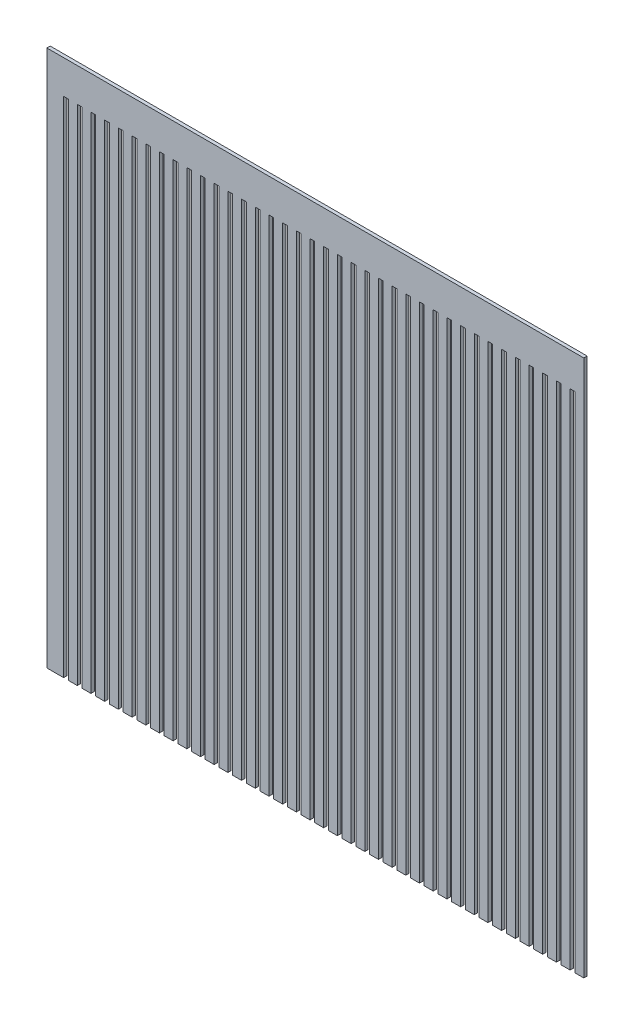
SolidWorks part; units mm, degrees
ref_plane "前视基准面" through (0, 0, 0) normal (0, 0, 1) x (1, 0, 0)
ref_plane "上视基准面" through (0, 0, 0) normal (0, 1, 0) x (1, 0, 0)
ref_plane "右视基准面" through (0, 0, 0) normal (1, 0, 0) x (0, 0, -1)
sketch "草图1" plane through (0, 0, 0) normal (0, 0, 1) x (1, 0, 0)
  line L0 (-74.9927, 70) -> (-74.9927, -80)
  line L2 (-79.9927, -80) -> (-79.9927, 80)
  line L3 (-79.9927, 80) -> (80.0073, 80)
  line L4 (80.0073, -80) -> (80.0073, 80)
  line L5 (-69.5137, -80) -> (-69.5137, 70)
  line L6 (-70.9137, 70) -> (-70.9137, -80)
  line L7 (-70.9137, 70) -> (-69.5137, 70)
  line L8 (-73.5927, -80) -> (-73.5927, 70)
  line L9 (-74.9927, -80) -> (-79.9927, -80)
  line L10 (-74.9927, 70) -> (-73.5927, 70)
  line L11 (-65.4348, -80) -> (-65.4348, 70)
  line L13 (-74.2927, -80) -> (-74.2927, 72.603) construction
  line L14 (-66.8348, 70) -> (-66.8348, -80)
  line L15 (-66.8348, 70) -> (-65.4348, 70)
  line L17 (-73.5927, 70) -> (-73.5927, -80)
  line L19 (-74.9927, -80) -> (-79.9927, -80)
  line L20 (-61.3558, -80) -> (-61.3558, 70)
  line L21 (-62.7558, 70) -> (-62.7558, -80)
  line L22 (-62.7558, 70) -> (-61.3558, 70)
  line L23 (-57.2769, -80) -> (-57.2769, 70)
  line L24 (-58.6769, 70) -> (-58.6769, -80)
  line L25 (-58.6769, 70) -> (-57.2769, 70)
  line L26 (-53.1979, -80) -> (-53.1979, 70)
  line L27 (-54.5979, 70) -> (-54.5979, -80)
  line L28 (-54.5979, 70) -> (-53.1979, 70)
  line L29 (-49.119, -80) -> (-49.119, 70)
  line L30 (-50.519, 70) -> (-50.519, -80)
  line L31 (-50.519, 70) -> (-49.119, 70)
  line L32 (-45.04, -80) -> (-45.04, 70)
  line L33 (-46.44, 70) -> (-46.44, -80)
  line L34 (-46.44, 70) -> (-45.04, 70)
  line L35 (-40.9611, -80) -> (-40.9611, 70)
  line L36 (-42.3611, 70) -> (-42.3611, -80)
  line L37 (-42.3611, 70) -> (-40.9611, 70)
  line L38 (-36.8821, -80) -> (-36.8821, 70)
  line L39 (-38.2821, 70) -> (-38.2821, -80)
  line L40 (-38.2821, 70) -> (-36.8821, 70)
  line L41 (-32.8032, -80) -> (-32.8032, 70)
  line L42 (-34.2032, 70) -> (-34.2032, -80)
  line L43 (-34.2032, 70) -> (-32.8032, 70)
  line L44 (-28.7242, -80) -> (-28.7242, 70)
  line L45 (-30.1242, 70) -> (-30.1242, -80)
  line L46 (-30.1242, 70) -> (-28.7242, 70)
  line L47 (-24.6453, -80) -> (-24.6453, 70)
  line L48 (-26.0453, 70) -> (-26.0453, -80)
  line L49 (-26.0453, 70) -> (-24.6453, 70)
  line L50 (-20.5663, -80) -> (-20.5663, 70)
  line L51 (-21.9663, 70) -> (-21.9663, -80)
  line L52 (-21.9663, 70) -> (-20.5663, 70)
  line L53 (-16.4874, -80) -> (-16.4874, 70)
  line L54 (-17.8874, 70) -> (-17.8874, -80)
  line L55 (-17.8874, 70) -> (-16.4874, 70)
  line L56 (-12.4084, -80) -> (-12.4084, 70)
  line L57 (-13.8084, 70) -> (-13.8084, -80)
  line L58 (-13.8084, 70) -> (-12.4084, 70)
  line L59 (-8.3295, -80) -> (-8.3295, 70)
  line L60 (-9.7295, 70) -> (-9.7295, -80)
  line L61 (-9.7295, 70) -> (-8.3295, 70)
  line L62 (-4.2506, -80) -> (-4.2506, 70)
  line L63 (-5.6506, 70) -> (-5.6506, -80)
  line L64 (-5.6506, 70) -> (-4.2506, 70)
  line L65 (-0.1716, -80) -> (-0.1716, 70)
  line L66 (-1.5716, 70) -> (-1.5716, -80)
  line L67 (-1.5716, 70) -> (-0.1716, 70)
  line L68 (3.9073, -80) -> (3.9073, 70)
  line L69 (2.5073, 70) -> (2.5073, -80)
  line L70 (2.5073, 70) -> (3.9073, 70)
  line L71 (7.9863, -80) -> (7.9863, 70)
  line L72 (6.5863, 70) -> (6.5863, -80)
  line L73 (6.5863, 70) -> (7.9863, 70)
  line L74 (12.0652, -80) -> (12.0652, 70)
  line L75 (10.6652, 70) -> (10.6652, -80)
  line L76 (10.6652, 70) -> (12.0652, 70)
  line L77 (16.1442, -80) -> (16.1442, 70)
  line L78 (14.7442, 70) -> (14.7442, -80)
  line L79 (14.7442, 70) -> (16.1442, 70)
  line L80 (20.2231, -80) -> (20.2231, 70)
  line L81 (18.8231, 70) -> (18.8231, -80)
  line L82 (18.8231, 70) -> (20.2231, 70)
  line L83 (24.3021, -80) -> (24.3021, 70)
  line L84 (22.9021, 70) -> (22.9021, -80)
  line L85 (22.9021, 70) -> (24.3021, 70)
  line L86 (28.381, -80) -> (28.381, 70)
  line L87 (26.981, 70) -> (26.981, -80)
  line L88 (26.981, 70) -> (28.381, 70)
  line L89 (32.46, -80) -> (32.46, 70)
  line L90 (31.06, 70) -> (31.06, -80)
  line L91 (31.06, 70) -> (32.46, 70)
  line L92 (36.5389, -80) -> (36.5389, 70)
  line L93 (35.1389, 70) -> (35.1389, -80)
  line L94 (35.1389, 70) -> (36.5389, 70)
  line L95 (40.6179, -80) -> (40.6179, 70)
  line L96 (39.2179, 70) -> (39.2179, -80)
  line L97 (39.2179, 70) -> (40.6179, 70)
  line L98 (44.6968, -80) -> (44.6968, 70)
  line L99 (43.2968, 70) -> (43.2968, -80)
  line L100 (43.2968, 70) -> (44.6968, 70)
  line L101 (48.7758, -80) -> (48.7758, 70)
  line L102 (47.3758, 70) -> (47.3758, -80)
  line L103 (47.3758, 70) -> (48.7758, 70)
  line L104 (52.8547, -80) -> (52.8547, 70)
  line L105 (51.4547, 70) -> (51.4547, -80)
  line L106 (51.4547, 70) -> (52.8547, 70)
  line L107 (56.9337, -80) -> (56.9337, 70)
  line L108 (55.5337, 70) -> (55.5337, -80)
  line L109 (55.5337, 70) -> (56.9337, 70)
  line L110 (61.0126, -80) -> (61.0126, 70)
  line L111 (59.6126, 70) -> (59.6126, -80)
  line L112 (59.6126, 70) -> (61.0126, 70)
  line L113 (65.0916, -80) -> (65.0916, 70)
  line L114 (63.6916, 70) -> (63.6916, -80)
  line L115 (63.6916, 70) -> (65.0916, 70)
  line L116 (69.1705, -80) -> (69.1705, 70)
  line L117 (67.7705, 70) -> (67.7705, -80)
  line L118 (67.7705, 70) -> (69.1705, 70)
  line L119 (73.2494, -80) -> (73.2494, 70)
  line L120 (71.8494, 70) -> (71.8494, -80)
  line L121 (71.8494, 70) -> (73.2494, 70)
  line L122 (77.3284, -80) -> (77.3284, 70)
  line L123 (75.9284, 70) -> (75.9284, -80)
  line L124 (75.9284, 70) -> (77.3284, 70)
  line L125 (-73.5927, -80) -> (-70.9137, -80)
  line L126 (-69.5137, -80) -> (-66.8348, -80)
  line L127 (-65.4348, -80) -> (-62.7558, -80)
  line L128 (-61.3558, -80) -> (-58.6769, -80)
  line L129 (-57.2769, -80) -> (-54.5979, -80)
  line L130 (-53.1979, -80) -> (-50.519, -80)
  line L131 (-49.119, -80) -> (-46.44, -80)
  line L132 (-45.04, -80) -> (-42.3611, -80)
  line L133 (-40.9611, -80) -> (-38.2821, -80)
  line L134 (-36.8821, -80) -> (-34.2032, -80)
  line L135 (-32.8032, -80) -> (-30.1242, -80)
  line L136 (-28.7242, -80) -> (-26.0453, -80)
  line L137 (-24.6453, -80) -> (-21.9663, -80)
  line L138 (-20.5663, -80) -> (-17.8874, -80)
  line L139 (-16.4874, -80) -> (-13.8084, -80)
  line L140 (-12.4084, -80) -> (-9.7295, -80)
  line L141 (-8.3295, -80) -> (-5.6506, -80)
  line L142 (-4.2506, -80) -> (-1.5716, -80)
  line L143 (-0.1716, -80) -> (2.5073, -80)
  line L144 (3.9073, -80) -> (6.5863, -80)
  line L145 (7.9863, -80) -> (10.6652, -80)
  line L146 (12.0652, -80) -> (14.7442, -80)
  line L147 (16.1442, -80) -> (18.8231, -80)
  line L148 (20.2231, -80) -> (22.9021, -80)
  line L149 (24.3021, -80) -> (26.981, -80)
  line L150 (28.381, -80) -> (31.06, -80)
  line L151 (32.46, -80) -> (35.1389, -80)
  line L152 (36.5389, -80) -> (39.2179, -80)
  line L153 (40.6179, -80) -> (43.2968, -80)
  line L154 (44.6968, -80) -> (47.3758, -80)
  line L155 (48.7758, -80) -> (51.4547, -80)
  line L156 (52.8547, -80) -> (55.5337, -80)
  line L157 (56.9337, -80) -> (59.6126, -80)
  line L158 (61.0126, -80) -> (63.6916, -80)
  line L159 (65.0916, -80) -> (67.7705, -80)
  line L160 (69.1705, -80) -> (71.8494, -80)
  line L161 (73.2494, -80) -> (75.9284, -80)
  line L162 (77.3284, -80) -> (80.0073, -80)
  point P0 (79.9152, -80)
  dimension "D1" = 160
  dimension "D2" = 160
  dimension "D3" = 1.4
  dimension "D4" = 5
  dimension "D7" = 10
extrude "凸台-拉伸2" add sketch "草图1" along normal blind 1
